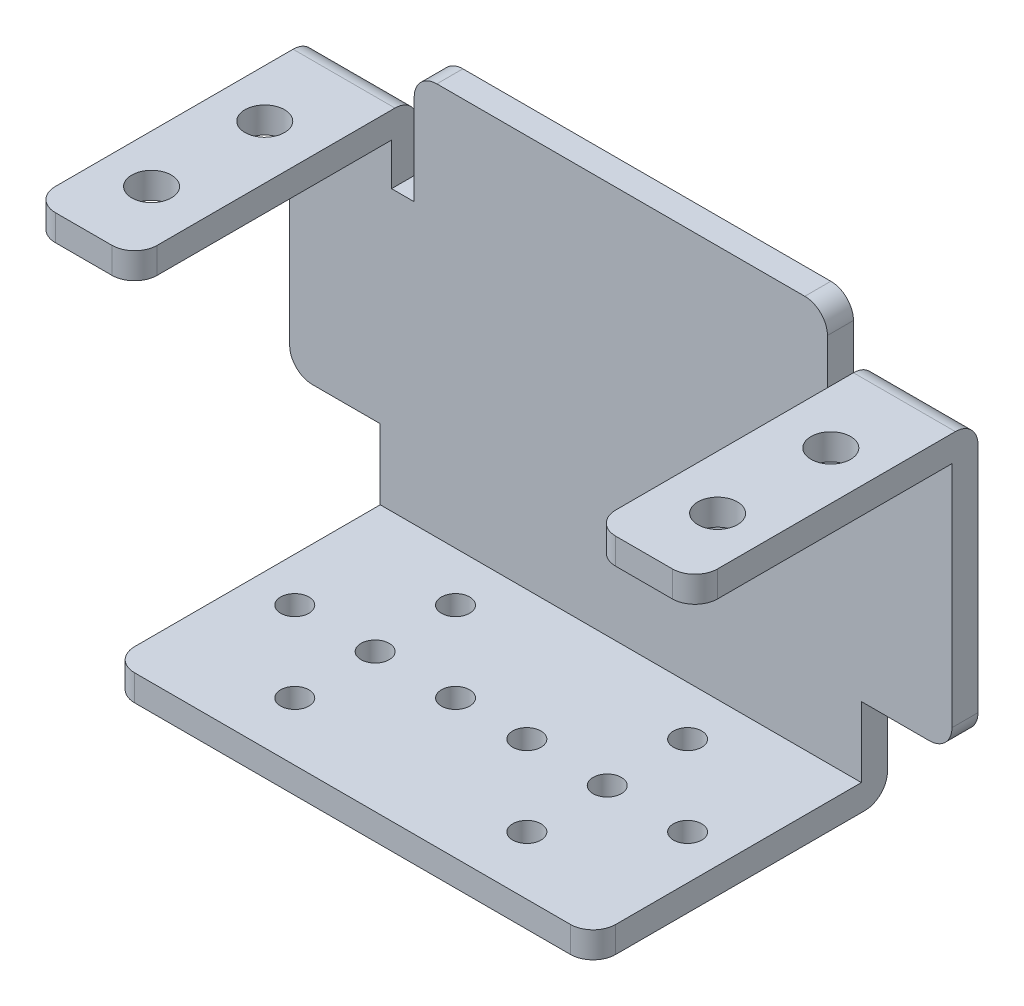
SolidWorks part; units mm, degrees
ref_plane "前视基准面" through (0, 0, 0) normal (0, 0, 1) x (1, 0, 0)
ref_plane "上视基准面" through (0, 0, 0) normal (0, 1, 0) x (1, 0, 0)
ref_plane "右视基准面" through (0, 0, 0) normal (1, 0, 0) x (0, 0, -1)
sketch "草图2" plane through (0, 0, 0) normal (0, 1, 0) x (1, 0, 0)
  line L1 (-21.25, 13) -> (21.25, 13)
  line L2 (-21.25, 13) -> (-21.25, -13)
  line L3 (-21.25, -13) -> (21.25, -13)
  line L4 (21.25, 13) -> (21.25, -13)
  line L5 (-21.25, 13) -> (21.25, -13) construction
  line L6 (-21.25, -13) -> (21.25, 13) construction
  point P0 (0, 0)
  dimension "D1" = 42.5
  dimension "D2" = 26
extrude "凸台-拉伸1" add sketch "草图2" along normal blind 2.3
sketch "草图3" plane through (0, 0, -13) normal (0, 0, -1) x (-1, 0, 0)
  line L0 (20.25, 33) -> (20.25, 26.9815)
  line L1 (-21.25, 0) -> (21.25, 0)
  line L2 (-21.25, 0) -> (-21.25, 8.5)
  line L3 (-20.25, 26.9815) -> (-18.25, 26.9815)
  line L4 (21.25, 0) -> (21.25, 8.5)
  line L5 (21.25, 8.5) -> (29.25, 8.5)
  line L6 (29.25, 8.5) -> (29.25, 33)
  line L7 (29.25, 33) -> (20.25, 33)
  line L8 (0, 50.1674) -> (0, -9.7013) construction
  line L9 (-18.25, 26.9815) -> (-18.25, 37)
  line L10 (-18.25, 37) -> (18.25, 37)
  line L11 (18.25, 26.9815) -> (18.25, 37)
  line L12 (18.25, 26.9815) -> (20.25, 26.9815)
  line L13 (-21.25, 8.5) -> (-29.25, 8.5)
  line L14 (-20.25, 33) -> (-20.25, 26.9815)
  line L15 (-29.25, 33) -> (-20.25, 33)
  line L16 (-29.25, 8.5) -> (-29.25, 33)
  point P13 (0, 37)
  point P22 (20.1917, 26.9793)
  dimension "D1" = 27
  dimension "D2" = 8.5
  dimension "D3" = 36.5
  dimension "D4" = 37
  dimension "D5" = 8
  dimension "D6" = 24.5
  dimension "D7" = 1
extrude "凸台-拉伸3" add sketch "草图3" against normal blind 2.3
sketch "草图5" plane through (0, 0, -13) normal (0, 0, -1) x (-1, 0, 0)
  line L0 (-20.25, 26.9815) -> (-20.25, 33) construction
  line L1 (-29.25, 33) -> (-20.25, 33)
  line L2 (-29.25, 33) -> (-29.25, 30.7)
  line L3 (-29.25, 30.7) -> (-20.25, 30.7)
  line L4 (-20.25, 33) -> (-20.25, 30.7)
  line L5 (29.25, 8.5) -> (29.25, 33) construction
  line L6 (20.25, 33) -> (29.25, 33)
  line L7 (20.25, 33) -> (20.25, 30.7)
  line L8 (20.25, 30.7) -> (29.25, 30.7)
  line L9 (29.25, 33) -> (29.25, 30.7)
  dimension "D1" = 2.3
  dimension "D2" = 2.3
extrude "凸台-拉伸6" add sketch "草图5" against normal blind 25
fillet "圆角1" radius 2 13 edges at (29.25, 8.5, -11.85) (-29.25, 8.5, -11.85) (-21.25, 1.15, 13) (21.25, 1.15, 13) (0, 0, -13) (-18.25, 37, -11.85) (18.25, 37, -11.85) (-24.75, 33, -13) (24.75, 33, -13) (29.25, 31.85, 12) (20.25, 31.85, 12) (-20.25, 31.85, 12) (-29.25, 31.85, 12)
sketch "草图6" plane through (0, 33, 0) normal (0, 1, 0) x (1, 0, 0)
  line L0 (-27.25, -12) -> (-22.25, -12) construction
  line L1 (-21.25, 10.7) -> (-21.25, -11) construction
  circle A0 centre (-25, -5.75) radius 1.75
  circle A1 centre (-25, 4.25) radius 1.75
  dimension "D2" = 3.5
  dimension "D1" = 4.5
  dimension "D3" = 2
  dimension "D4" = 13.5
extrude "切除-拉伸1" cut sketch "草图6" against normal up to next
sketch "草图7" plane through (0, 2.3, 0) normal (0, 1, 0) x (1, 0, 0)
  line L0 (-21.25, 10.7) -> (-21.25, -11) construction
  line L1 (-19.25, -13) -> (19.25, -13) construction
  circle A0 centre (-10.25, -0.75) radius 1.25
  circle A1 centre (-10.25, -7.85) radius 1.25
  circle A2 centre (-17.35, -0.75) radius 1.25
  circle A3 centre (-10.25, 6.35) radius 1.25
  circle A4 centre (-3.15, -0.75) radius 1.25
  point P17 (-10.25, -0.75)
  dimension "D1" = 2.5
  dimension "D2" = 9.75
  dimension "D3" = 11
  dimension "D4" = 7.1
  dimension "D5" = 4
extrude "切除-拉伸2" cut sketch "草图7" against normal up to next
mirror "镜向1" about plane through (0, 0, 0) normal (1, 0, 0) of "切除-拉伸2", "切除-拉伸1"
